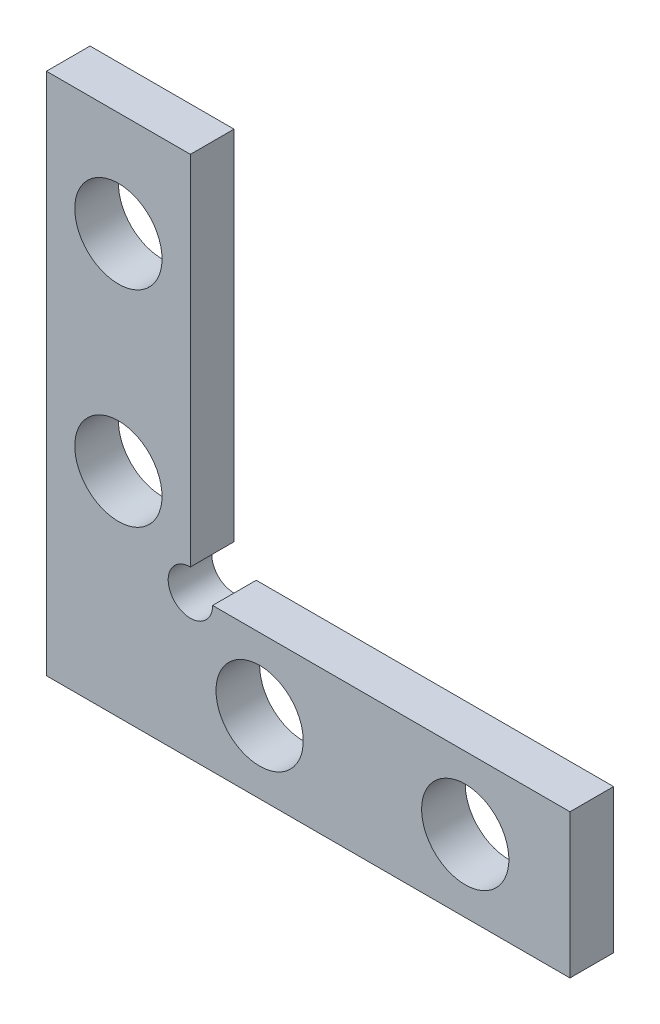
SolidWorks part; units mm, degrees
ref_plane "前视基准面" through (0, 0, 0) normal (0, 0, 1) x (1, 0, 0)
ref_plane "上视基准面" through (0, 0, 0) normal (0, 1, 0) x (1, 0, 0)
ref_plane "右视基准面" through (0, 0, 0) normal (1, 0, 0) x (0, 0, -1)
sketch "草图1" plane through (0, 0, 0) normal (0, 0, 1) x (1, 0, 0)
  line L1 (0, 0) -> (9.9, 0)
  line L2 (0, 0) -> (0, 36)
  line L3 (0, 36) -> (9.9, 36)
  line L4 (9.9, 0) -> (9.9, 36)
  dimension "D1" = 9.9
  dimension "D2" = 36
extrude "凸台-拉伸1" add sketch "草图1" along normal blind 3
sketch "草图2" plane through (0, 0, 3) normal (0, 0, 1) x (1, 0, 0)
  line L1 (0, 0) -> (36, 0)
  line L2 (0, 0) -> (0, 9.9)
  line L3 (0, 9.9) -> (36, 9.9)
  line L4 (36, 0) -> (36, 9.9)
  dimension "D1" = 9.9
  dimension "D2" = 36
extrude "凸台-拉伸2" add sketch "草图2" against normal blind 3
sketch "草图3" plane through (0, 0, 3) normal (0, 0, 1) x (1, 0, 0)
  line L0 (9.9, 9.9) -> (0, 0) construction
  circle A0 centre (4.95, 28.7978) radius 3
  circle A1 centre (4.95, 14.6614) radius 3
  circle A2 centre (14.6614, 4.95) radius 3
  circle A3 centre (28.7978, 4.95) radius 3
  dimension "D1" = 6
  dimension "D2" = 6
extrude "切除-拉伸1" cut sketch "草图3" against normal through all
sketch "草图4" plane through (0, 0, 3) normal (0, 0, 1) x (1, 0, 0)
  circle A0 centre (9.9, 9.9) radius 1.5271
extrude "切除-拉伸2" cut sketch "草图4" against normal through all
